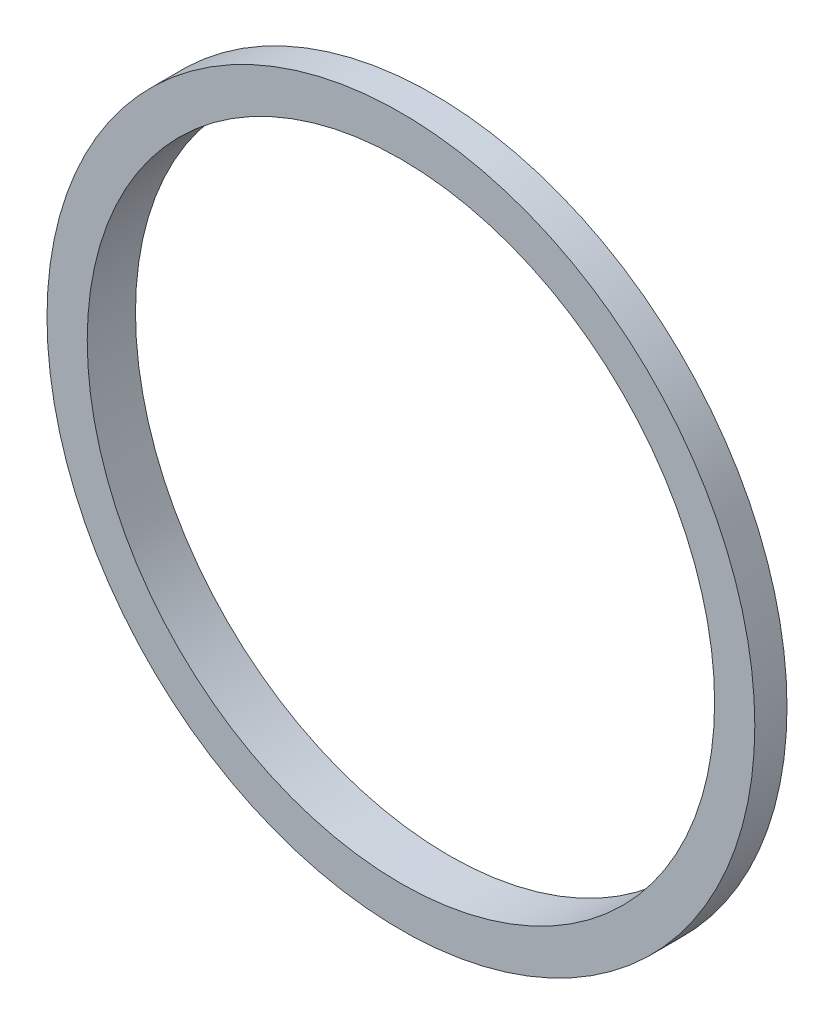
SolidWorks part; units mm, degrees
ref_plane "Front Plane" through (0, 0, 0) normal (0, 0, 1) x (1, 0, 0)
ref_plane "Top Plane" through (0, 0, 0) normal (0, 1, 0) x (1, 0, 0)
ref_plane "Right Plane" through (0, 0, 0) normal (1, 0, 0) x (0, 0, -1)
sketch "Sketch1" plane through (0, 0, 0) normal (0, 0, 1) x (1, 0, 0)
  circle A0 centre (0, 0) radius 22
  dimension "D1" = 44
extrude "Boss-Extrude2" add sketch "Sketch1" along normal blind 2
sketch "Sketch4" plane through (0, 0, 0) normal (0, 0, -1) x (-1, 0, 0)
  circle A0 centre (0, 0) radius 20.5
  dimension "D1" = 41
extrude "Boss-Extrude3" add sketch "Sketch4" along normal blind 1
sketch "Sketch5" plane through (0, 0, -1) normal (0, 0, -1) x (-1, 0, 0)
  circle A0 centre (0, 0) radius 19.5
  dimension "D1" = 39
extrude "Cut-Extrude1" cut sketch "Sketch5" against normal through all
